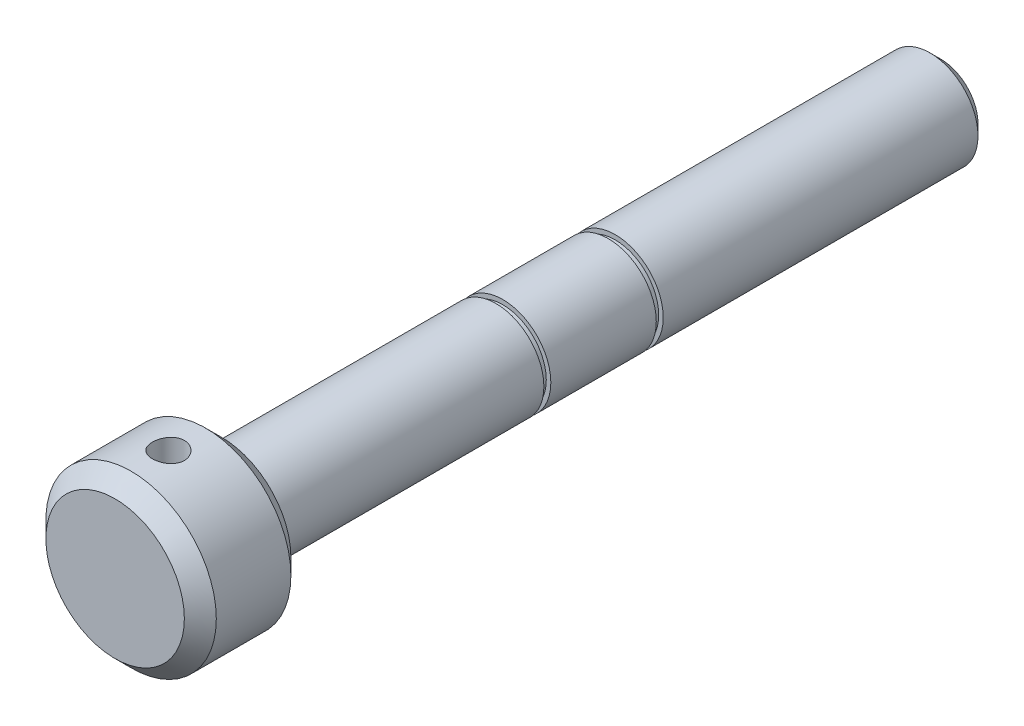
SolidWorks part; units mm, degrees
ref_plane "Piano frontale" through (0, 0, 0) normal (0, 0, 1) x (1, 0, 0)
ref_plane "Piano superiore" through (0, 0, 0) normal (0, 1, 0) x (1, 0, 0)
ref_plane "Piano destro" through (0, 0, 0) normal (1, 0, 0) x (0, 0, -1)
sketch "Schizzo2" plane through (0, 0, 0) normal (0, 0, 1) x (1, 0, 0)
  circle A0 centre (0, 0) radius 9
  dimension "D1" = 18
extrude "Estrusione-Estrusione1" add sketch "Schizzo2" along normal blind 135
cosmetic thread "Filettatura cosmetica1" parameters "D2"=15.252
sketch "Schizzo3" plane through (0, 0, 135) normal (0, 0, 1) x (1, 0, 0)
  circle A0 centre (0, 0) radius 16
  dimension "D1" = 32
extrude "Estrusione-Estrusione2" add sketch "Schizzo3" along normal blind 20
ref_plane "Piano1" through (0, 16, 0) normal (0, 1, 0) x (1, 0, 0)
sketch "Schizzo4" plane through (0, 16, 0) normal (0, 1, 0) x (1, 0, 0)
  line L0 (0, -135) -> (0, -155) construction
  line L1 (16, -135) -> (-16, -135) construction
  line L2 (-16, -155) -> (16, -155) construction
  circle A0 centre (0, -145) radius 3
  dimension "D1" = 6
extrude "Taglio-Estrusione1" cut sketch "Schizzo4" against normal up to next
chamfer "Smusso1" distance 3 angle 45 2 edges at (16, 0, 155) (16, 0, 135)
chamfer "Smusso2" distance 2 angle 45 1 edges at (9, 0, 0)
ref_plane "Piano2" through (0, 0, 83.5) normal (0, 0, 1) x (1, 0, 0)
sketch "Schizzo6" plane through (0, 0, 83.5) normal (0, 0, 1) x (1, 0, 0)
  circle A0 centre (0, 0) radius 8.15
  circle A1 centre (0, 0) radius 9
  dimension "D1" = 16.3
  dimension "D2" = 18
extrude "Taglio-Estrusione2" cut sketch "Schizzo6" against normal blind 1.3
ref_plane "Piano3" through (0, 0, 72.3) normal (0, 0, -1) x (-1, 0, 0)
mirror "Specchia1" about plane through (0, 0, 72.3) normal (0, 0, -1) of "Taglio-Estrusione2"
